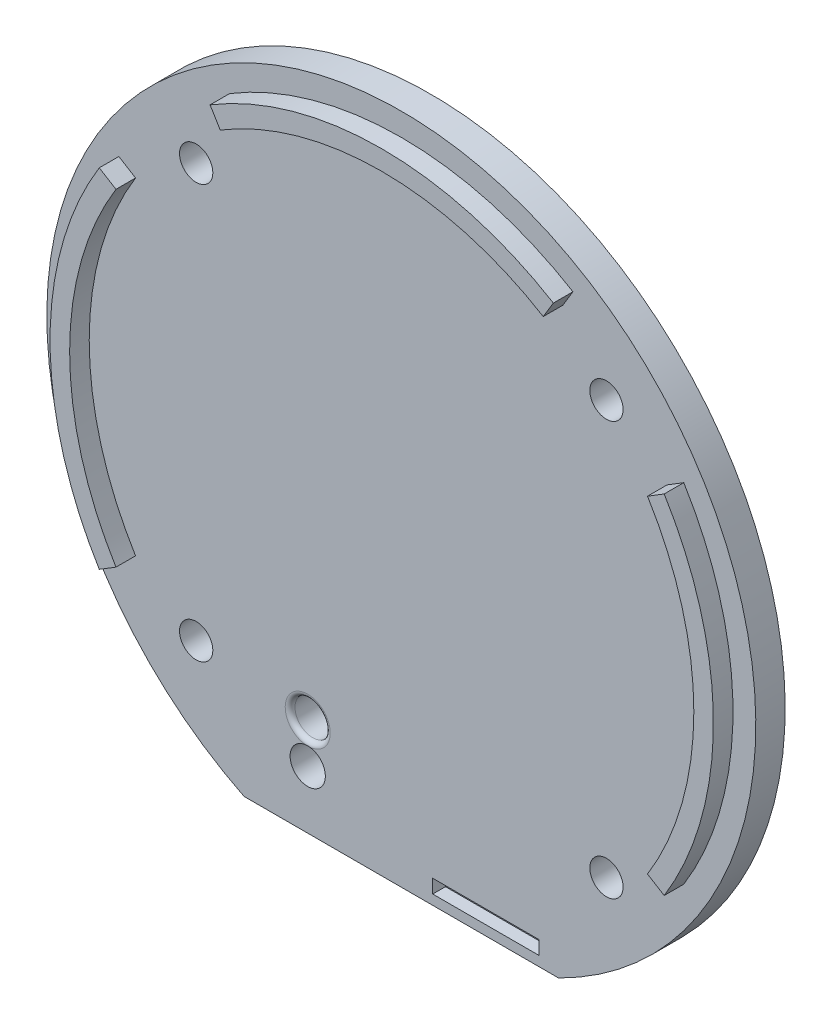
SolidWorks part; units mm, degrees
ref_plane "Front" through (0, 0, 0) normal (0, 0, 1) x (1, 0, 0)
ref_plane "Top" through (0, 0, 0) normal (0, 1, 0) x (1, 0, 0)
ref_plane "Right" through (0, 0, 0) normal (1, 0, 0) x (0, 0, -1)
sketch "Sketch1" plane through (0, 0, 0) normal (0, 0, 1) x (1, 0, 0)
  line L2 (36.21, 0) -> (-36.21, 0) construction
  line L3 (-16.06, -32.4537) -> (16.06, -32.4537)
  arc A1 (16.06, -32.4537) -> (-16.06, -32.4537) centre (0, 0) ccw
  point P6 (0, 0)
  dimension "D1" = 36.21
  dimension "D3" = 32.12
extrude "Boss-Extrude1" add sketch "Sketch1" along normal blind 3 contours A1 L3
sketch "Sketch2" plane through (0, 0, 3) normal (0, 0, 1) x (1, 0, 0)
  line L0 (0, 36.21) -> (0, 0) construction
  line L1 (-20.955, 21.12) -> (20.955, 21.12) construction
  line L2 (-36.21, 0) -> (36.21, 0) construction
  line L3 (-20.955, 21.12) -> (-20.955, -21.12) construction
  arc A0 (16.06, -32.4537) -> (-16.06, -32.4537) centre (0, 0) ccw construction
  circle A1 centre (-20.955, 21.12) radius 1.7
  circle A2 centre (20.955, 21.12) radius 1.7
  circle A5 centre (-20.955, -21.12) radius 1.7
  circle A6 centre (20.955, -21.12) radius 1.7
  point P8 (0, 21.12)
  dimension "D3" = 3.4
  dimension "D1" = 15.09
  dimension "D2" = 41.91
  dimension "D4" = 42.24
extrude "Cut-Extrude1" cut sketch "Sketch2" against normal up to surface (3 mm away) up to face at (0, 1.8782, 0)
sketch "Sketch4" plane through (0, 0, 3) normal (0, 0, 1) x (1, 0, 0)
  line L1 (0, 36.21) -> (0, -32.4537) construction
  line L2 (-17.5341, 28.9898) -> (-16.4991, 27.2785)
  line L4 (-28.8514, 17.761) -> (-27.1482, 16.7125)
  line L5 (-28.8514, -17.761) -> (-27.1482, -16.7125)
  line L7 (-16.06, -32.4537) -> (16.06, -32.4537) construction
  line L8 (17.5341, 28.9898) -> (16.4991, 27.2785)
  line L9 (-36.21, 0) -> (36.21, 0) construction
  line L10 (28.8514, 17.761) -> (27.1482, 16.7125)
  line L11 (28.8514, -17.761) -> (27.1482, -16.7125)
  arc A0 (-28.8514, 17.761) -> (-28.8514, -17.761) centre (0, 0) ccw
  arc A1 (16.06, -32.4537) -> (-16.06, -32.4537) centre (0, 0) ccw construction
  arc A2 (-27.1482, 16.7125) -> (-27.1482, -16.7125) centre (0, 0) ccw
  arc A3 (16.4991, 27.2785) -> (-16.4991, 27.2785) centre (0, 0) ccw
  arc A4 (16.06, -32.4537) -> (-16.06, -32.4537) centre (0, 0) ccw construction
  arc A5 (17.5341, 28.9898) -> (-17.5341, 28.9898) centre (0, 0) ccw
  circle A6 centre (-20.955, 21.12) radius 1.7 construction
  circle A7 centre (20.955, 21.12) radius 1.7 construction
  arc A8 (28.8514, 17.761) -> (28.8514, -17.761) centre (0, 0) cw
  arc A9 (27.1482, 16.7125) -> (27.1482, -16.7125) centre (0, 0) cw
  point P13 (0, 33.88)
  point P16 (-33.88, 0)
  point P29 (0, 36.21)
  dimension "D2" = 2.33
  dimension "D3" = 2
  dimension "D4" = 7
  dimension "D5" = 7
  dimension "D1" = 2
extrude "Boss-Extrude2" add sketch "Sketch4" along normal blind 2
sketch "Sketch6" plane through (0, 0, 0) normal (0, 0, -1) x (-1, 0, 0)
  line L0 (9.56, -32.4537) -> (9.56, -22.4537) construction
  line L1 (16.06, -32.4537) -> (-16.06, -32.4537) construction
  circle A0 centre (9.56, -22.4537) radius 1.8
  circle A1 centre (9.56, -26.5237) radius 1.8
  dimension "D3" = 3.6
  dimension "D1" = 10
  dimension "D2" = 6.5
  dimension "D4" = 4.07
extrude "Cut-Extrude2" cut sketch "Sketch6" against normal up to surface (3 mm away) up to face at (19.255, 21.12, 3)
sketch "Sketch8" plane through (0, 0, 3) normal (0, 0, 1) x (1, 0, 0)
  line L0 (-16.06, -32.4537) -> (16.06, -32.4537) construction
  line L1 (3.21, -31.4537) -> (14.06, -31.4537)
  line L2 (3.21, -31.4537) -> (3.21, -30.0537)
  line L3 (3.21, -30.0537) -> (14.06, -30.0537)
  line L4 (14.06, -31.4537) -> (14.06, -30.0537)
  line L5 (16.06, -32.4537) -> (16.06, -24.7151) construction
  dimension "D1" = 1
  dimension "D2" = 10.85
  dimension "D3" = 1.4
  dimension "D4" = 2
extrude "Cut-Extrude4" cut sketch "Sketch8" against normal blind 1.3
fillet "Fillet2" radius 0.5 1 edges at (-7.76, -22.4537, 3)
